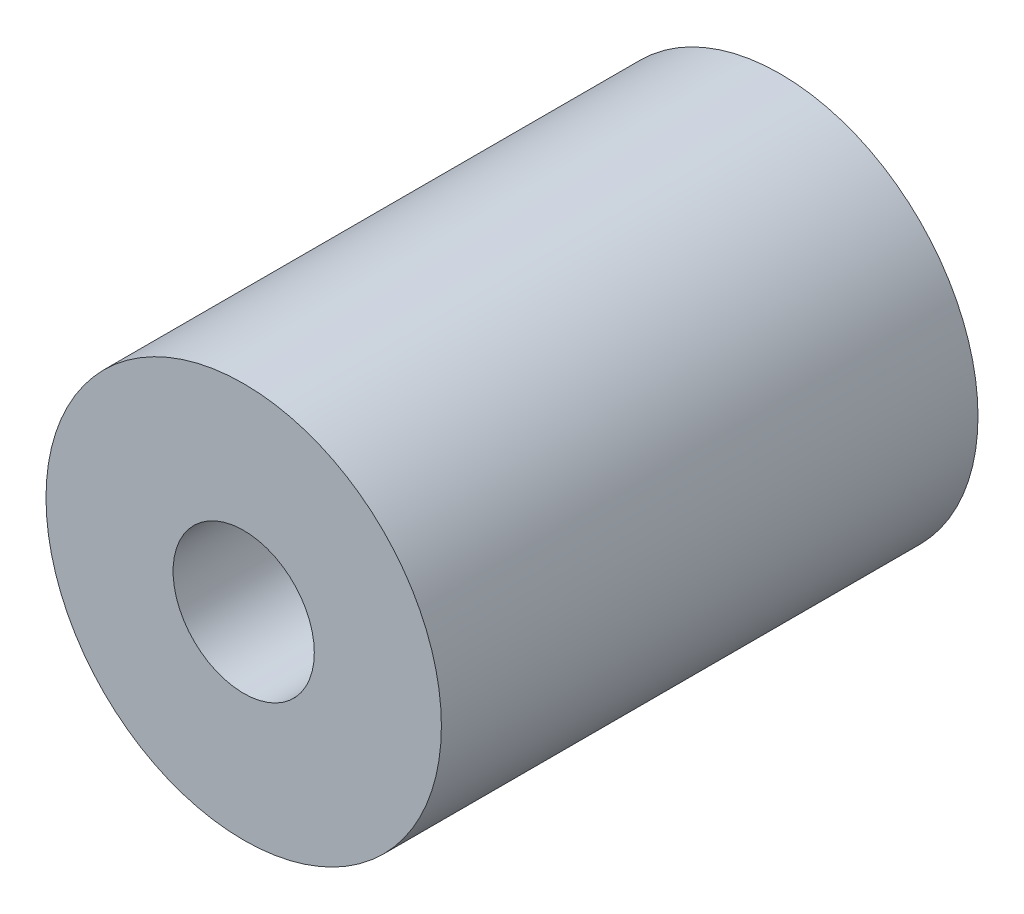
SolidWorks part; units mm, degrees
material "SKD11淬火HRC56-60"
ref_plane "前基準面" through (0, 0, 0) normal (0, 0, 1) x (1, 0, 0)
ref_plane "上基準面" through (0, 0, 0) normal (0, 1, 0) x (1, 0, 0)
ref_plane "右基準面" through (0, 0, 0) normal (1, 0, 0) x (0, 0, -1)
sketch "草图1" plane through (0, 0, 0) normal (0, 0, 1) x (1, 0, 0)
  circle A0 centre (0, 0) radius 14
  circle A1 centre (0, 0) radius 5
  dimension "D1" = 28
  dimension "D2" = 10
extrude "凸台-拉伸1" add sketch "草图1" along normal blind 38
